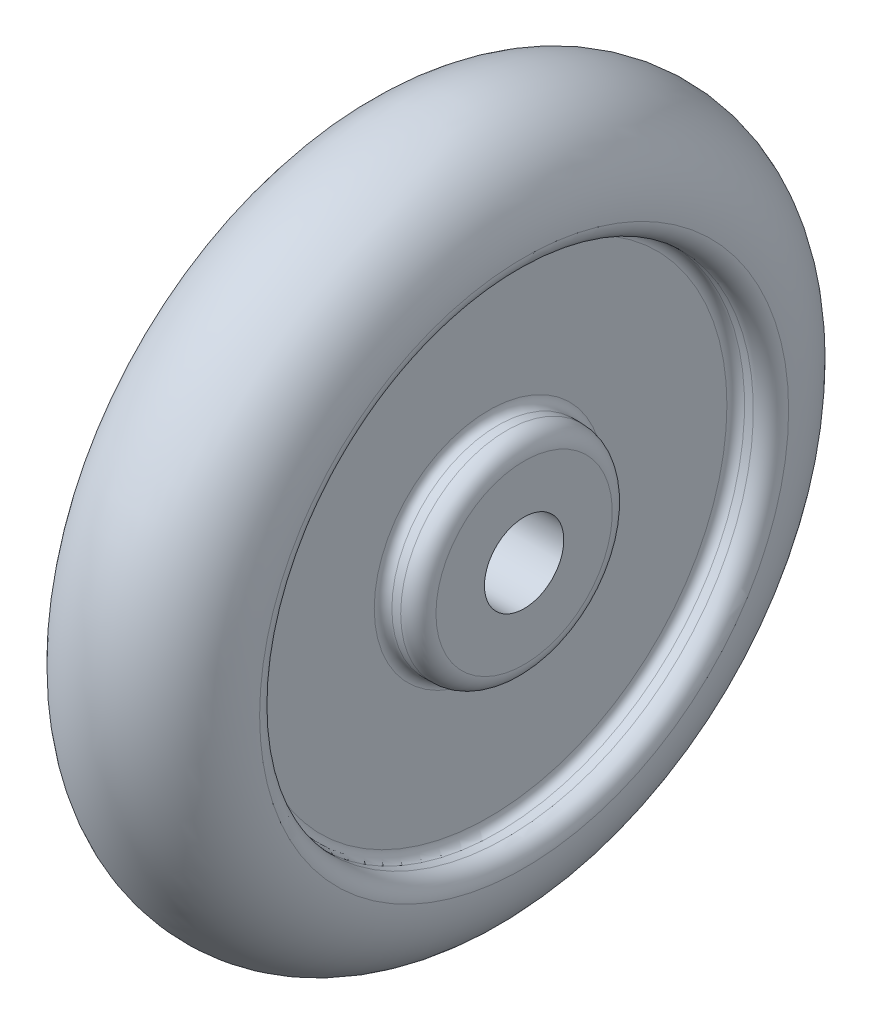
SolidWorks part; units mm, degrees
ref_plane "Front Plane" through (0, 0, 0) normal (0, 0, 1) x (1, 0, 0)
ref_plane "Top Plane" through (0, 0, 0) normal (0, 1, 0) x (1, 0, 0)
ref_plane "Right Plane" through (0, 0, 0) normal (1, 0, 0) x (0, 0, -1)
sketch "Sketch1" plane through (0, 0, 0) normal (0, 0, 1) x (1, 0, 0)
  line L2 (-4, 14) -> (-3.5, 14)
  line L3 (-3, 13.5) -> (-3, 6.5)
  line L4 (-3.5, 6) -> (-4, 6)
  line L5 (-5, 5) -> (-5, 2.25)
  line L6 (-5, 2.25) -> (5, 2.25)
  line L7 (0, 15) -> (0, 0) construction
  line L8 (5, 5) -> (5, 2.25)
  line L9 (3.5, 6) -> (4, 6)
  line L10 (3, 13.5) -> (3, 6.5)
  line L11 (4, 14) -> (3.5, 14)
  line L12 (-8.9228, 0) -> (10.2562, 0) construction
  arc A0 (5, 15) -> (-5, 15) centre (0, 15) ccw
  arc A1 (-5, 15) -> (-4, 14) centre (-4, 15) ccw
  arc A2 (-4, 6) -> (-5, 5) centre (-4, 5) ccw
  arc A3 (5, 5) -> (4, 6) centre (4, 5) ccw
  arc A4 (4, 14) -> (5, 15) centre (4, 15) ccw
  arc A5 (3, 13.5) -> (3.5, 14) centre (3.5, 13.5) cw
  arc A6 (-3.5, 14) -> (-3, 13.5) centre (-3.5, 13.5) cw
  arc A7 (3.5, 6) -> (3, 6.5) centre (3.5, 6.5) cw
  arc A8 (-3, 6.5) -> (-3.5, 6) centre (-3.5, 6.5) cw
  point P12 (0, 2.25)
  point P16 (0, 20)
  point P19 (-5, 12.9579)
  point P22 (-5, 6)
  point P25 (5, 6)
  point P28 (5, 12.9579)
  point P31 (3, 14)
  point P34 (-3, 14)
  point P37 (3, 6)
  point P40 (-3, 6)
  dimension "D1" = 5
  dimension "D3" = 0.5
  dimension "D5" = 1
  dimension "D6" = 1
  dimension "D8" = 0.5
  dimension "D2" = 20
  dimension "D4" = 2.25
  dimension "D7" = 6
revolve "Revolve1" add sketch "Sketch1" angle 360 about L12
